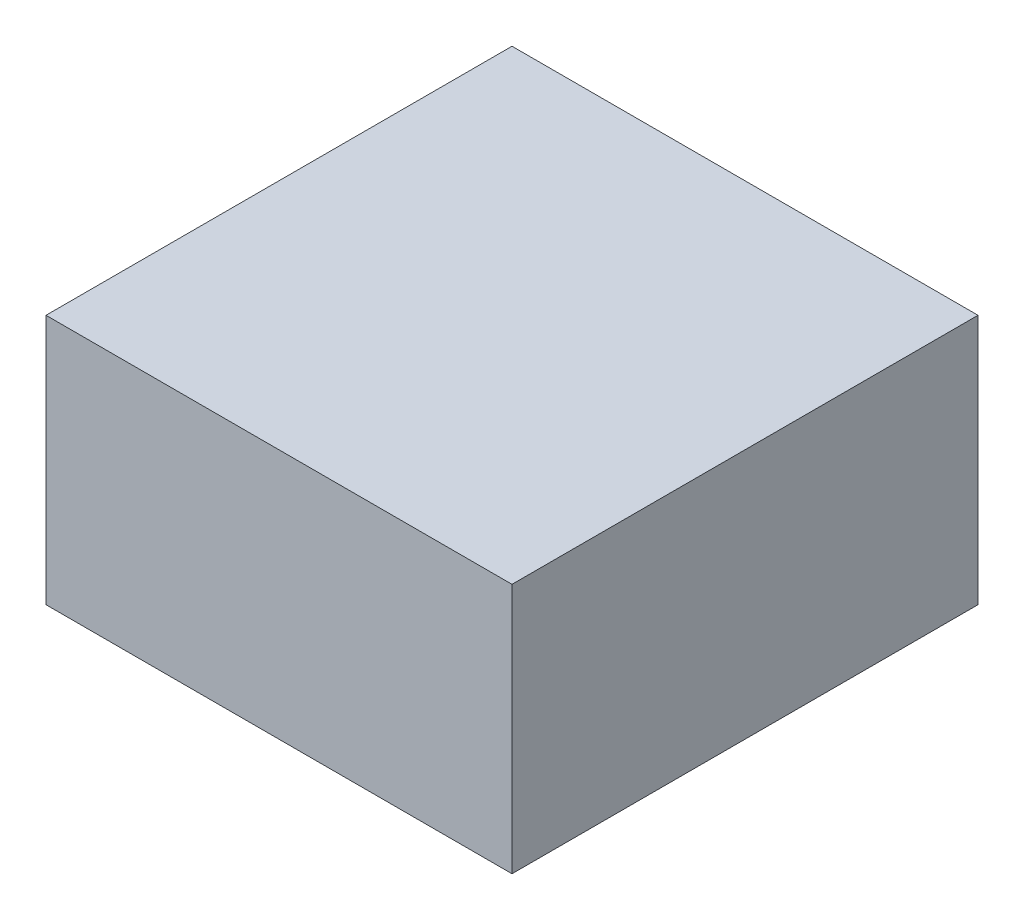
SolidWorks part; units mm, degrees
material "Pine"
ref_plane "Ön Düzlem" through (0, 0, 0) normal (0, 0, 1) x (1, 0, 0)
ref_plane "Üst Düzlem" through (0, 0, 0) normal (0, 1, 0) x (1, 0, 0)
ref_plane "Sağ Düzlem" through (0, 0, 0) normal (1, 0, 0) x (0, 0, -1)
sketch "Çizim1" plane through (0, 0, 0) normal (0, 1, 0) x (1, 0, 0)
  line L1 (-72.5, -72.5) -> (72.5, -72.5)
  line L2 (-72.5, -72.5) -> (-72.5, 72.5)
  line L3 (-72.5, 72.5) -> (72.5, 72.5)
  line L4 (72.5, -72.5) -> (72.5, 72.5)
  line L5 (-72.5, -72.5) -> (72.5, 72.5) construction
  line L6 (-72.5, 72.5) -> (72.5, -72.5) construction
  point P0 (0, 0)
  dimension "D1" = 145
  dimension "D2" = 145
extrude "Yükseklik-Ekstrüzyon1" add sketch "Çizim1" along normal blind 78
